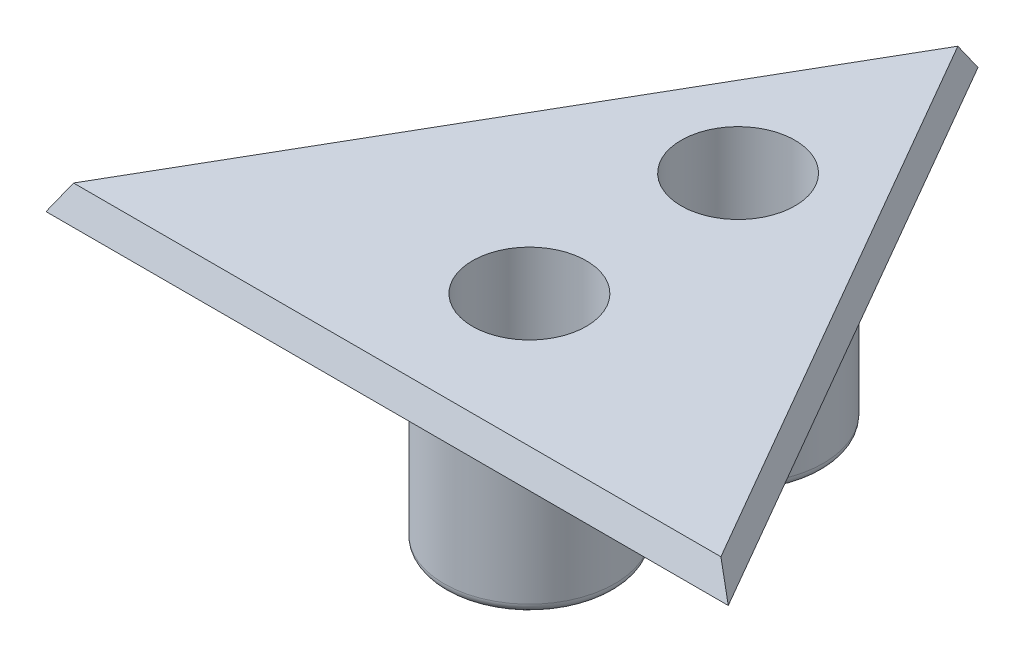
SolidWorks part; units mm, degrees
ref_plane "Front Plane" through (0, 0, 0) normal (0, 0, 1) x (1, 0, 0)
ref_plane "Top Plane" through (0, 0, 0) normal (0, 1, 0) x (1, 0, 0)
ref_plane "Right Plane" through (0, 0, 0) normal (1, 0, 0) x (0, 0, -1)
sketch "Sketch1" plane through (0, 0, 0) normal (0, 1, 0) x (1, 0, 0)
  line L1 (0, 41.5282) -> (-35.9645, -20.7641)
  line L2 (-35.9645, -20.7641) -> (35.9645, -20.7641)
  line L3 (35.9645, -20.7641) -> (0, 41.5282)
  circle A0 centre (0, 0) radius 20.7641 construction
  dimension "D1" = 71.929
extrude "Boss-Extrude1" add sketch "Sketch1" along normal blind 3 draft 19.5
sketch "Sketch3" plane through (0, 3, 0) normal (0, 1, 0) x (1, 0, 0)
  line L0 (-35.9645, -20.7641) -> (35.9645, -20.7641) construction
  line L1 (0, 16.2359) -> (0, 1.0511) construction
  circle A0 centre (0, 16.2359) radius 9
  dimension "D1" = 18
  dimension "D2" = 37
extrude "Boss-Extrude2" add sketch "Sketch3" against normal blind 20 from surface at -3 starting at face at (0, 0, 0)
sketch "Sketch4" plane through (0, 3, 0) normal (0, 1, 0) x (1, 0, 0)
  circle A0 centre (0, 16.2359) radius 6
  dimension "D1" = 12
extrude "Cut-Extrude1" cut sketch "Sketch4" against normal blind 10
hole_wizard "M12 Tapped Hole1" positions "Sketch7" profile "Sketch6" tap size "M12" standard "ISO" end condition through all
sketch "Sketch7" plane through (0, -20, 0) normal (0, -1, 0) x (-1, 0, 0)
  circle A0 centre (0, 16.2359) radius 9 construction
  point P0 (0, 16.2359)
sketch "Sketch6" plane through (0, -20, -16.2359) normal (1, 0, 0) x (0, 0, -1)
  line L0 (0, 0) -> (0, 23)
  line L1 (0, 23) -> (5.1, 23)
  line L2 (5.1, 23) -> (5.1, 0)
  line L5 (5.1, 0) -> (0, 0)
  line L11 (0, -6.35) -> (0, 107.95) construction
  dimension "Thru Tap Drill Dia." = 10.2
  dimension "Thru Tap Drill Depth" = 23
cosmetic thread "Hole Thread1" parameters "D2"=12
fillet "Fillet1" radius 1 1 edges at (0, -20, -7.2359)
fillet "Fillet2" radius 0.5 1 edges at (0, 0, -7.2359)
sketch "Sketch8" plane through (0, 3, 0) normal (0, 1, 0) x (1, 0, 0)
  line L0 (0, 39.4035) -> (0, -19.7018) construction
  line L1 (-34.1244, -19.7018) -> (34.1244, -19.7018) construction
pattern_linear "LPattern1" count 2 spacing 22 along (0, 0, 1) of "Boss-Extrude2", "Fillet2", "Cut-Extrude1", "Fillet1", "M12 Tapped Hole1"
